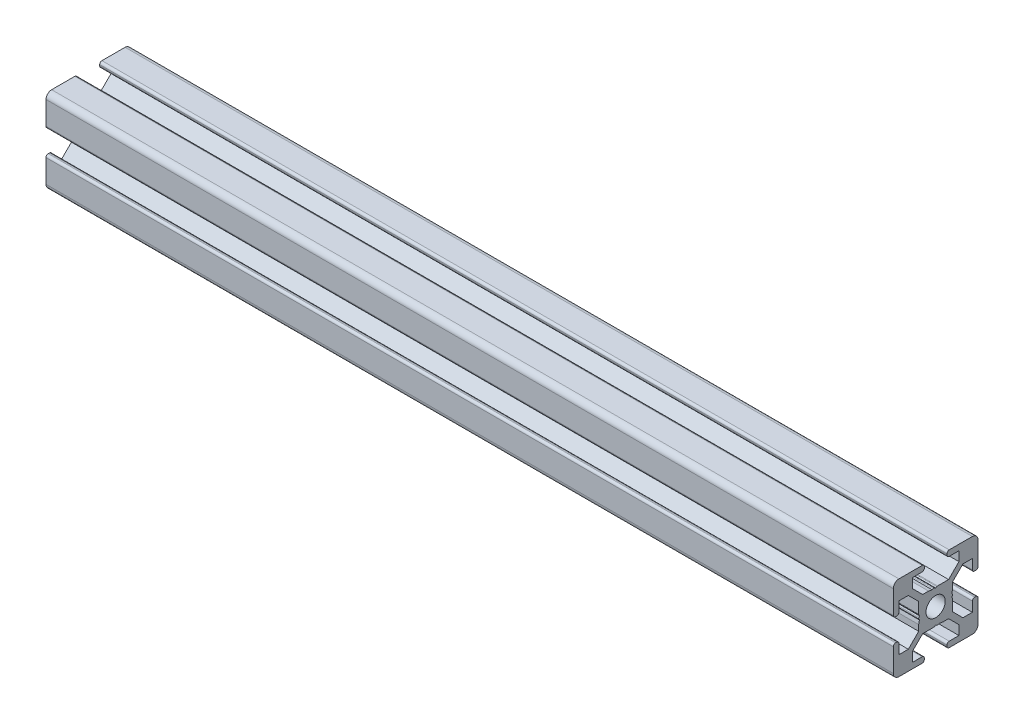
SolidWorks part; units mm, degrees
ref_plane "前视基准面" through (0, 0, 0) normal (0, 0, 1) x (1, 0, 0)
ref_plane "上视基准面" through (0, 0, 0) normal (0, 1, 0) x (1, 0, 0)
ref_plane "右视基准面" through (0, 0, 0) normal (1, 0, 0) x (0, 0, -1)
sketch "草图3" plane through (0, 0, 0) normal (0, 1, 0) x (1, 0, 0)
  line L0 (-150, 0) -> (150, 0)
  point P3 (119.3431, 0)
  point P4 (0, 0)
  dimension "D1" = 300
other "铝型材 30 X 30 X R2(2)"
ref_plane "基准面2" through (-150, 0, 0) normal (1, 0, 0) x (0, 0, -1)
sketch "草图1" plane through (-150, 0, 0) normal (1, 0, 0) x (0, 0, -1)
  line L0 (-15, -4.8) -> (-15, -13)
  line L1 (-13, -15) -> (-4.8, -15)
  line L2 (-4, -14.2) -> (-4, -13.8)
  line L3 (-4.8, -13) -> (-8.25, -13)
  line L4 (-8.25, -13) -> (-8.25, -9.6642)
  line L5 (-8.25, -9.6642) -> (-4.5858, -6)
  line L6 (-4.5858, -6) -> (-0.6536, -6)
  line L7 (-0.4036, -5.933) -> (0, -5.7)
  line L8 (0, -5.7) -> (0.4036, -5.933)
  line L9 (0.9036, -5.933) -> (1.2189, -5.751)
  line L10 (1.2189, -5.751) -> (2.5, -6)
  line L11 (2.5, -6) -> (4.5858, -6)
  line L12 (4.5858, -6) -> (8.25, -9.6642)
  line L13 (8.25, -9.6642) -> (8.25, -13)
  line L14 (8.25, -13) -> (4.8, -13)
  line L15 (4, -13.8) -> (4, -14.2)
  line L16 (4.8, -15) -> (13, -15)
  line L17 (15, -13) -> (15, -4.8)
  line L18 (14.2, -4) -> (13.8, -4)
  line L19 (13, -4.8) -> (13, -8.25)
  line L20 (13, -8.25) -> (9.6642, -8.25)
  line L21 (9.6642, -8.25) -> (6, -4.5858)
  line L22 (6, -4.5858) -> (6, -0.6536)
  line L23 (5.933, -0.4036) -> (5.7, 0)
  line L24 (5.7, 0) -> (5.933, 0.4036)
  line L25 (5.933, 0.9036) -> (5.751, 1.2189)
  line L26 (5.751, 1.2189) -> (6, 2.5)
  line L27 (6, 2.5) -> (6, 4.5858)
  line L28 (6, 4.5858) -> (9.6642, 8.25)
  line L29 (9.6642, 8.25) -> (13, 8.25)
  line L30 (13, 8.25) -> (13, 4.8)
  line L31 (13.8, 4) -> (14.2, 4)
  line L32 (15, 4.8) -> (15, 13)
  line L33 (13, 15) -> (4.8, 15)
  line L34 (4, 14.2) -> (4, 13.8)
  line L35 (4.8, 13) -> (8.25, 13)
  line L36 (8.25, 13) -> (8.25, 9.6642)
  line L37 (8.25, 9.6642) -> (4.5858, 6)
  line L38 (4.5858, 6) -> (0.6536, 6)
  line L39 (0.4036, 5.933) -> (0, 5.7)
  line L40 (0, 5.7) -> (-0.4036, 5.933)
  line L41 (-0.9036, 5.933) -> (-1.2189, 5.751)
  line L42 (-1.2189, 5.751) -> (-2.5, 6)
  line L43 (-2.5, 6) -> (-4.5858, 6)
  line L44 (-4.5858, 6) -> (-8.25, 9.6642)
  line L45 (-8.25, 9.6642) -> (-8.25, 13)
  line L46 (-8.25, 13) -> (-4.8, 13)
  line L47 (-4, 13.8) -> (-4, 14.2)
  line L48 (-4.8, 15) -> (-13, 15)
  line L49 (-15, 13) -> (-15, 4.8)
  line L50 (-14.2, 4) -> (-13.8, 4)
  line L51 (-13, 4.8) -> (-13, 8.25)
  line L52 (-13, 8.25) -> (-9.6642, 8.25)
  line L53 (-9.6642, 8.25) -> (-6, 4.5858)
  line L54 (-6, 4.5858) -> (-6, 0.6536)
  line L55 (-5.933, 0.4036) -> (-5.7, 0)
  line L56 (-5.7, 0) -> (-5.933, -0.4036)
  line L57 (-5.933, -0.9036) -> (-5.751, -1.2189)
  line L58 (-5.751, -1.2189) -> (-6, -2.5)
  line L59 (-6, -2.5) -> (-6, -4.5858)
  line L60 (-6, -4.5858) -> (-9.6642, -8.25)
  line L61 (-9.6642, -8.25) -> (-13, -8.25)
  line L62 (-13, -8.25) -> (-13, -4.8)
  line L63 (-13.8, -4) -> (-14.2, -4)
  arc A0 (-15, -13) -> (-13, -15) centre (-13, -13) ccw
  arc A1 (-4.8, -15) -> (-4, -14.2) centre (-4.8, -14.2) ccw
  arc A2 (-4, -13.8) -> (-4.8, -13) centre (-4.8, -13.8) ccw
  arc A3 (-0.6536, -6) -> (-0.4036, -5.933) centre (-0.6536, -5.5) ccw
  arc A4 (0.4036, -5.933) -> (0.9036, -5.933) centre (0.6536, -5.5) ccw
  arc A5 (4.8, -13) -> (4, -13.8) centre (4.8, -13.8) ccw
  arc A6 (4, -14.2) -> (4.8, -15) centre (4.8, -14.2) ccw
  arc A7 (13, -15) -> (15, -13) centre (13, -13) ccw
  arc A8 (15, -4.8) -> (14.2, -4) centre (14.2, -4.8) ccw
  arc A9 (13.8, -4) -> (13, -4.8) centre (13.8, -4.8) ccw
  arc A10 (6, -0.6536) -> (5.933, -0.4036) centre (5.5, -0.6536) ccw
  arc A11 (5.933, 0.4036) -> (5.933, 0.9036) centre (5.5, 0.6536) ccw
  arc A12 (13, 4.8) -> (13.8, 4) centre (13.8, 4.8) ccw
  arc A13 (14.2, 4) -> (15, 4.8) centre (14.2, 4.8) ccw
  arc A14 (15, 13) -> (13, 15) centre (13, 13) ccw
  arc A15 (4.8, 15) -> (4, 14.2) centre (4.8, 14.2) ccw
  arc A16 (4, 13.8) -> (4.8, 13) centre (4.8, 13.8) ccw
  arc A17 (0.6536, 6) -> (0.4036, 5.933) centre (0.6536, 5.5) ccw
  arc A18 (-0.4036, 5.933) -> (-0.9036, 5.933) centre (-0.6536, 5.5) ccw
  arc A19 (-4.8, 13) -> (-4, 13.8) centre (-4.8, 13.8) ccw
  arc A20 (-4, 14.2) -> (-4.8, 15) centre (-4.8, 14.2) ccw
  arc A21 (-13, 15) -> (-15, 13) centre (-13, 13) ccw
  arc A22 (-15, 4.8) -> (-14.2, 4) centre (-14.2, 4.8) ccw
  arc A23 (-13.8, 4) -> (-13, 4.8) centre (-13.8, 4.8) ccw
  arc A24 (-6, 0.6536) -> (-5.933, 0.4036) centre (-5.5, 0.6536) ccw
  arc A25 (-5.933, -0.4036) -> (-5.933, -0.9036) centre (-5.5, -0.6536) ccw
  arc A26 (-13, -4.8) -> (-13.8, -4) centre (-13.8, -4.8) ccw
  arc A27 (-14.2, -4) -> (-15, -4.8) centre (-14.2, -4.8) ccw
  circle A28 centre (0, 0) radius 3.4
  point P123 (0, 0)
  dimension "D3" = 6.8
  dimension "D1" = 30
  dimension "D2" = 30
